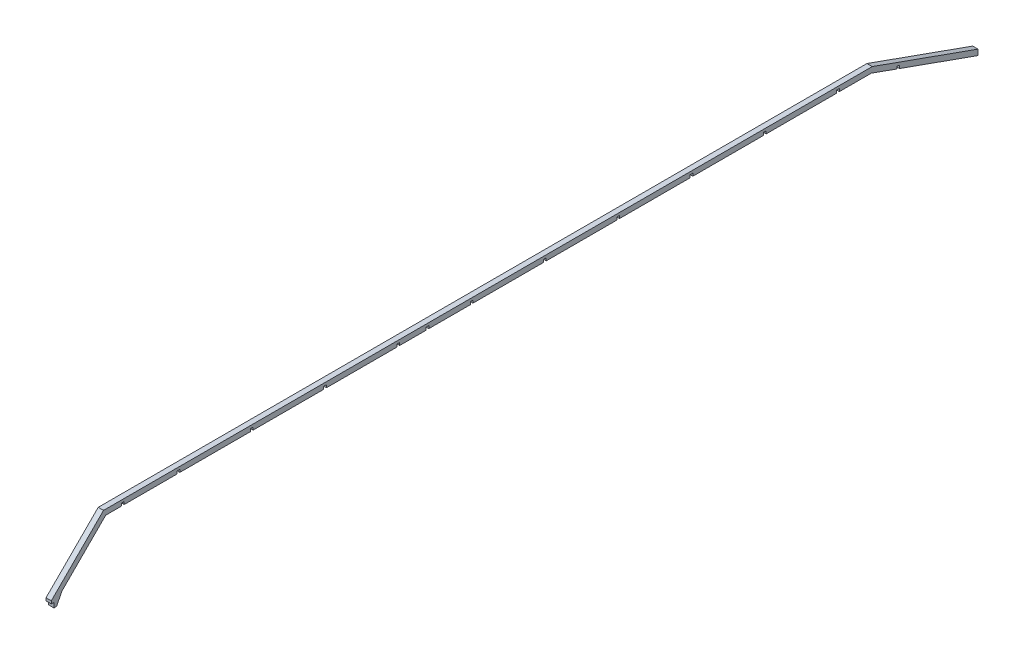
SolidWorks part; units mm, degrees
ref_plane "Спереди" through (0, 0, 0) normal (0, 0, 1) x (1, 0, 0)
ref_plane "Сверху" through (0, 0, 0) normal (0, 1, 0) x (1, 0, 0)
ref_plane "Справа" through (0, 0, 0) normal (1, 0, 0) x (0, 0, -1)
other "Configuration Table"
sketch "Эскиз1" plane through (0, 0, 0) normal (1, 0, 0) x (0, 0, -1)
  line L0 (-751.8866, -19.1422) -> (-733.9606, -19.1422)
  line L1 (115.1734, -19.1422) -> (144.0394, -29.4493)
  line L6 (160.4534, -35.3102) -> (162.4711, -29.6596) construction
  line L7 (-813.5251, -80.7807) -> (-751.8866, -19.1422) construction
  line L8 (-813.5251, -72.2954) -> (-813.5251, -80.7807) construction
  line L17 (147.0394, -30.5205) -> (147.0394, -27.5205)
  line L18 (147.0394, -27.5205) -> (144.0394, -26.4493)
  line L19 (144.0394, -26.4493) -> (144.0394, -29.4493)
  line L20 (147.0394, -30.5205) -> (236.0394, -62.2995)
  line L21 (79.0394, -19.1422) -> (79.0394, -16.1422)
  line L22 (79.0394, -16.1422) -> (76.0394, -16.1422)
  line L23 (76.0394, -16.1422) -> (76.0394, -19.1422)
  line L24 (79.0394, -19.1422) -> (115.1734, -19.1422)
  line L25 (-3.9606, -19.1422) -> (-3.9606, -16.1422)
  line L26 (-3.9606, -16.1422) -> (-6.9606, -16.1422)
  line L27 (-6.9606, -16.1422) -> (-6.9606, -19.1422)
  line L28 (-86.9606, -19.1422) -> (-86.9606, -16.1422)
  line L29 (-86.9606, -16.1422) -> (-89.9606, -16.1422)
  line L30 (-89.9606, -16.1422) -> (-89.9606, -19.1422)
  line L31 (-169.9606, -19.1422) -> (-169.9606, -16.1422)
  line L32 (-169.9606, -16.1422) -> (-172.9606, -16.1422)
  line L33 (-172.9606, -16.1422) -> (-172.9606, -19.1422)
  line L34 (-252.9606, -19.1422) -> (-252.9606, -16.1422)
  line L35 (-252.9606, -16.1422) -> (-255.9606, -16.1422)
  line L36 (-255.9606, -16.1422) -> (-255.9606, -19.1422)
  line L37 (-335.9606, -19.1422) -> (-335.9606, -16.1422)
  line L38 (-335.9606, -16.1422) -> (-338.9606, -16.1422)
  line L39 (-338.9606, -16.1422) -> (-338.9606, -19.1422)
  line L40 (-3.9606, -19.1422) -> (76.0394, -19.1422)
  line L41 (-86.9606, -19.1422) -> (-6.9606, -19.1422)
  line L42 (-169.9606, -19.1422) -> (-89.9606, -19.1422)
  line L43 (-252.9606, -19.1422) -> (-172.9606, -19.1422)
  line L44 (-335.9606, -19.1422) -> (-255.9606, -19.1422)
  line L45 (-385.9606, -19.1422) -> (-385.9606, -16.1422)
  line L46 (-385.9606, -16.1422) -> (-388.9606, -16.1422)
  line L47 (-388.9606, -16.1422) -> (-388.9606, -19.1422)
  line L48 (-385.9606, -19.1422) -> (-338.9606, -19.1422)
  line L49 (-418.9606, -19.1422) -> (-418.9606, -16.1422)
  line L50 (-418.9606, -16.1422) -> (-421.9606, -16.1422)
  line L51 (-421.9606, -16.1422) -> (-421.9606, -19.1422)
  line L52 (-418.9606, -19.1422) -> (-388.9606, -19.1422)
  line L53 (-501.9606, -19.1422) -> (-501.9606, -16.1422)
  line L54 (-501.9606, -16.1422) -> (-504.9606, -16.1422)
  line L55 (-504.9606, -16.1422) -> (-504.9606, -19.1422)
  line L56 (-584.9606, -19.1422) -> (-584.9606, -16.1422)
  line L57 (-584.9606, -16.1422) -> (-587.9606, -16.1422)
  line L58 (-587.9606, -16.1422) -> (-587.9606, -19.1422)
  line L59 (-667.9606, -19.1422) -> (-667.9606, -16.1422)
  line L60 (-667.9606, -16.1422) -> (-670.9606, -16.1422)
  line L61 (-670.9606, -16.1422) -> (-670.9606, -19.1422)
  line L62 (-501.9606, -19.1422) -> (-421.9606, -19.1422)
  line L63 (-584.9606, -19.1422) -> (-504.9606, -19.1422)
  line L64 (-667.9606, -19.1422) -> (-587.9606, -19.1422)
  line L65 (-730.9606, -19.1422) -> (-730.9606, -16.1422)
  line L66 (-730.9606, -16.1422) -> (-733.9606, -16.1422)
  line L67 (-733.9606, -16.1422) -> (-733.9606, -19.1422)
  line L68 (-730.9606, -19.1422) -> (-670.9606, -19.1422)
  line L69 (236.0394, -62.2995) -> (238.0571, -56.6489) construction
  line L70 (-3.9606, -19.1422) -> (-3.9606, -13.1422) construction
  line L71 (162.4711, -29.6596) -> (82.2261, -1.0067) construction
  line L72 (238.0571, -56.6489) -> (162.4711, -29.6596) construction
  line L73 (79.0394, -19.1422) -> (79.0394, -13.1422) construction
  line L74 (236.0394, -62.2995) -> (236.0394, -55.9285)
  line L75 (-3.9606, -13.1422) -> (116.2125, -13.1422) construction
  line L76 (-803.8198, -71.0753) -> (-808.0624, -66.8327) construction
  line L77 (-751.8866, -19.1422) -> (-756.1293, -14.8995) construction
  line L78 (-3.9606, -13.1422) -> (-770.7331, -13.1422) construction
  line L79 (-756.1293, -14.8995) -> (-813.5251, -72.2954) construction
  line L82 (-813.5251, -80.7807) -> (-801.5251, -80.7807) construction
  line L83 (-801.5251, -80.7807) -> (-801.5251, -68.7807) construction
  line L85 (-801.5251, -68.7807) -> (-751.8866, -19.1422)
  line L86 (-813.5251, -72.2954) -> (-754.3719, -13.1422)
  line L87 (-754.3719, -13.1422) -> (116.2125, -13.1422)
  line L88 (116.2125, -13.1422) -> (236.0394, -55.9285)
  line L90 (-810.5251, -75.2907) -> (-813.5251, -75.2907)
  line L91 (-813.5251, -75.2907) -> (-813.5251, -72.2954)
  line L93 (-810.5251, -75.2907) -> (-810.5251, -80.7807)
  line L94 (-810.5251, -80.7807) -> (-807.5251, -80.7807)
  line L95 (-807.5251, -80.7807) -> (-801.5251, -68.7807)
  point P49 (-388.9606, -17.6422)
  dimension "D1" = 160.35
  dimension "D2" = 128.34
  dimension "D4" = 6
  dimension "D5" = 6
  dimension "D6" = 867.06
  dimension "D7" = 6
  dimension "D11" = 81.17
  dimension "D12" = 3
  dimension "D13" = 65
  dimension "D14" = 3
  dimension "D15" = 3
  dimension "D16" = 3
  dimension "D17" = 80
  dimension "D18" = 3
  dimension "D19" = 80
  dimension "D20" = 3
  dimension "D21" = 80
  dimension "D22" = 3
  dimension "D23" = 80
  dimension "D24" = 3
  dimension "D25" = 80
  dimension "D26" = 3
  dimension "D27" = 47
  dimension "D28" = 3
  dimension "D29" = 3
  dimension "D30" = 30
  dimension "D31" = 3
  dimension "D32" = 80
  dimension "D33" = 3
  dimension "D34" = 80
  dimension "D35" = 80
  dimension "D36" = 3
  dimension "D37" = 3
  dimension "D38" = 60
  dimension "D39" = 6
  dimension "D40" = 6
extrude "Бобышка-Вытянуть3" add sketch "Эскиз1" along normal blind 6
